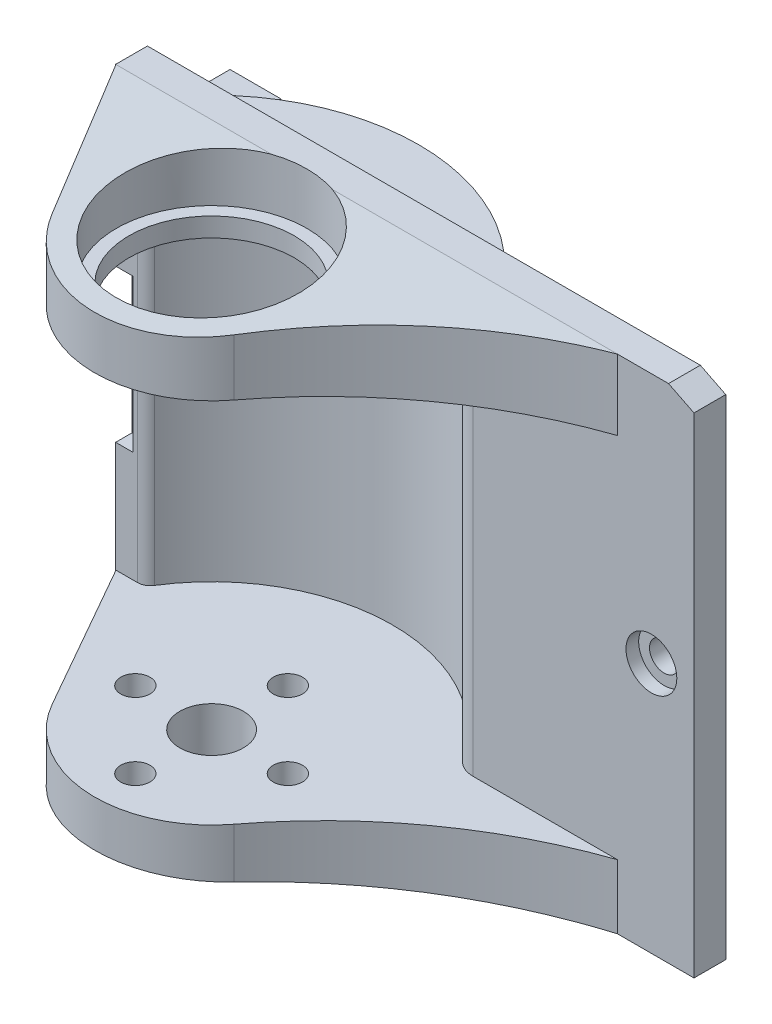
SolidWorks part; units mm, degrees
ref_plane "前视基准面" through (0, 0, 0) normal (0, 0, 1) x (1, 0, 0)
ref_plane "上视基准面" through (0, 0, 0) normal (0, 1, 0) x (1, 0, 0)
ref_plane "右视基准面" through (0, 0, 0) normal (1, 0, 0) x (0, 0, -1)
sketch "草图1" plane through (0, 0, 0) normal (0, 1, 0) x (1, 0, 0)
  circle A1 centre (0, 0) radius 16.3
  dimension "D1" = 32.6
extrude "凸台-拉伸1" add sketch "草图1" along normal mid plane 39.5
sketch "草图2" plane through (0, -19.75, 0) normal (0, -1, 0) x (1, 0, 0)
  line L1 (-14.65, -7.1) -> (31.85, -7.1)
  line L2 (-14.65, -7.1) -> (-14.65, -9.6)
  line L3 (-14.65, -9.6) -> (31.85, -9.6)
  line L4 (31.85, -7.1) -> (31.85, -9.6)
  dimension "D1" = 2.5
  dimension "D2" = 9.6
  dimension "D3" = 46.5
  dimension "D4" = 14.65
extrude "凸台-拉伸2" add sketch "草图2" against normal through all
sketch "草图3" plane through (0, -19.75, 0) normal (0, -1, 0) x (1, 0, 0)
  line L1 (31.85, -7.1) -> (-22.9944, -7.1)
  line L2 (31.85, -7.1) -> (31.85, 18.4067)
  line L3 (31.85, 18.4067) -> (-22.9944, 18.4067)
  line L4 (-22.9944, -7.1) -> (-22.9944, 18.4067)
extrude "切除-拉伸1" cut sketch "草图3" against normal blind 50
sketch "草图4" plane through (0, -19.75, 0) normal (0, -1, 0) x (1, 0, 0)
  line L0 (-14.65, -7.1462) -> (-7.9965, 4.5492)
  line L2 (-14.65, -7.1462) -> (24.85, -7.1078)
  line L3 (24.85, -7.1078) -> (24.85, 6.9283) construction
  arc A0 (7.3262, 5.5648) -> (-7.9965, 4.5492) centre (0, 0) ccw
  arc A2 (7.3262, 5.5648) -> (24.85, -7.1078) centre (36.9332, 28.0534) ccw
  dimension "D1" = 18.4
extrude "凸台-拉伸3" add sketch "草图4" against normal blind 5.05
mirror "镜向1" about plane through (0, 0, 0) normal (0, 1, 0) of "凸台-拉伸3"
sketch "草图5" plane through (0, -14.7, 0) normal (0, 1, 0) x (1, 0, 0)
  circle A0 centre (0, 0) radius 14.25
  dimension "D1" = 28.5
extrude "切除-拉伸2" cut sketch "草图5" along normal up to surface (29.4 mm away) up to face at (2.08, 14.7, -0.3156)
sketch "草图6" plane through (0, -14.7, 0) normal (0, 1, 0) x (1, 0, 0)
  circle A0 centre (0, 0) radius 2.5
  dimension "D1" = 5
extrude "切除-拉伸3" cut sketch "草图6" against normal through all
sketch "草图9" plane through (0, 19.75, 0) normal (0, 1, 0) x (1, 0, 0)
  circle A0 centre (0, 0) radius 7.5
  dimension "D1" = 15
extrude "切除-拉伸6" cut sketch "草图9" against normal up to next
sketch "草图12" plane through (0, 0, -7.1) normal (0, 0, 1) x (1, 0, 0)
  line L0 (0, 0) -> (30.0134, 0) construction
  line L1 (31.85, 19.75) -> (31.85, -19.75) construction
  circle A0 centre (27.5, 0) radius 1.15
  dimension "D1" = 2.3
  dimension "D2" = 4.35
extrude "切除-拉伸9" cut sketch "草图12" against normal through all
sketch "草图13" plane through (0, 0, -7.1) normal (0, 0, 1) x (1, 0, 0)
  circle A0 centre (27.5, 0) radius 2
  dimension "D1" = 4
extrude "切除-拉伸10" cut sketch "草图13" against normal blind 1
sketch "草图14" plane through (0, 0, -7.1) normal (0, 0, 1) x (1, 0, 0)
  line L0 (31.85, 19.75) -> (31.85, -19.75) construction
  line L1 (30.45, -6) -> (33.25, -6)
  line L2 (30.45, -6) -> (30.45, 6)
  line L3 (30.45, 6) -> (33.25, 6)
  line L4 (33.25, -6) -> (33.25, 6)
  line L5 (30.45, -6) -> (33.25, 6) construction
  line L6 (30.45, 6) -> (33.25, -6) construction
  point P0 (31.85, 0)
  dimension "12" = 12
  dimension "D2" = 2.8
extrude "切除-拉伸11" [suppressed] cut sketch "草图14" against normal blind 1.3
sketch "草图15" plane through (0, 0, -7.1) normal (0, 0, 1) x (1, 0, 0)
  line L0 (0, 0) -> (-23.1213, 0) construction
  line L1 (-14.6724, -19.75) -> (-14.6724, 19.75) construction
  line L2 (-16.0724, -6) -> (-13.2724, -6)
  line L3 (-16.0724, -6) -> (-16.0724, 6)
  line L4 (-16.0724, 6) -> (-13.2724, 6)
  line L5 (-13.2724, -6) -> (-13.2724, 6)
  line L6 (-16.0724, -6) -> (-13.2724, 6) construction
  line L7 (-16.0724, 6) -> (-13.2724, -6) construction
  point P3 (-14.6724, 0)
  dimension "D1" = 12
  dimension "D2" = 2.8
extrude "切除-拉伸12" cut sketch "草图15" against normal blind 1.3
ref_plane "基准面1" through (0, 0, -15.1) normal (0, 0, -1) x (-1, 0, 0)
sketch "草图16" plane through (0, 0, -15.1) normal (0, 0, -1) x (-1, 0, 0)
  line L0 (14.65, 19.75) -> (14.65, -19.75) construction
  line L1 (9.65, 10.9) -> (13.65, 10.9)
  line L2 (9.65, 10.9) -> (9.65, 15.9)
  line L3 (9.65, 15.9) -> (13.65, 15.9)
  line L4 (13.65, 10.9) -> (13.65, 15.9)
  line L5 (9.65, 10.9) -> (13.65, 15.9) construction
  line L6 (9.65, 15.9) -> (13.65, 10.9) construction
  line L7 (0, 0) -> (27.535, 0) construction
  point P0 (11.65, 13.4)
  dimension "D1" = 1
  dimension "D2" = 10.9
  dimension "D3" = 5
  dimension "D4" = 4
extrude "凸台-拉伸5" add sketch "草图16" against normal up to surface (1.9635 mm away)
mirror "镜向4" about plane through (0, 0, 0) normal (0, 1, 0) of "凸台-拉伸5"
sketch "草图17" plane through (0, 0, -15.1) normal (0, 0, -1) x (-1, 0, 0)
  line L0 (11.65, 15.9) -> (11.65, 12.48) construction
  line L1 (13.65, 15.9) -> (9.65, 15.9) construction
  line L2 (13.65, 13.4) -> (11.1035, 13.4) construction
  line L3 (13.65, 10.9) -> (13.65, 15.9) construction
  line L5 (11.15, 12.4) -> (12.15, 12.4)
  line L6 (11.15, 12.4) -> (11.15, 14.4)
  line L7 (11.15, 14.4) -> (12.15, 14.4)
  line L8 (12.15, 12.4) -> (12.15, 14.4)
  line L9 (11.15, 12.4) -> (12.15, 14.4) construction
  line L10 (11.15, 14.4) -> (12.15, 12.4) construction
  point P8 (11.65, 13.4)
  dimension "D1" = 2
  dimension "D2" = 1
extrude "切除-拉伸13" cut sketch "草图17" against normal blind 2.5
mirror "镜向5" about plane through (0, 0, 0) normal (0, 1, 0) of "切除-拉伸13"
sketch "草图19" plane through (0, 19.75, 0) normal (0, 1, 0) x (1, 0, 0)
  circle A1 centre (0, 0) radius 6.5
  circle A2 centre (0, 0) radius 8.519
  dimension "D1" = 13
extrude "凸台-拉伸6" add sketch "草图19" against normal blind 2.25
sketch "草图20" plane through (0, -19.75, 0) normal (0, -1, 0) x (1, 0, 0)
  circle A0 centre (0, 6) radius 1.15
  dimension "D1" = 2.3
  dimension "D2" = 6
extrude "切除-拉伸18" cut sketch "草图20" against normal up to next
pattern_circular "阵列(圆周)1" count 4 over 360 about axis through (0, 0, 0) along (0, 1, 0) of "切除-拉伸18"
sketch "草图7" plane through (-14.65, 0, 0) normal (-1, 0, 0) x (0, 0, 1)
  line L0 (-7.1, 19.75) -> (9.2, 18.3239)
  line L1 (9.2, 14.7) -> (9.2, 19.75) construction
  line L2 (9.2, 18.3239) -> (9.2, 19.75)
  line L3 (9.2, 19.75) -> (-7.1, 19.75)
  dimension "D1" = 5
extrude "切除-拉伸8" cut sketch "草图7" against normal through all
mirror "镜向3" about plane through (0, 0, 0) normal (0, 1, 0) of "切除-拉伸8"
sketch "草图18" plane through (0, 0, -9.6) normal (0, 0, -1) x (-1, 0, 0)
  line L0 (-13.1731, 19.75) -> (-13.1731, -19.75) construction
  line L1 (13.1731, 19.75) -> (-13.1731, 19.75)
  line L2 (13.1731, 19.75) -> (13.1731, 17)
  line L3 (13.1731, 17) -> (-13.1731, 17)
  line L4 (-13.1731, 19.75) -> (-13.1731, 17)
  dimension "D1" = 2.75
extrude "切除-拉伸16" cut sketch "草图18" along normal blind 12.5
mirror "镜向6" about plane through (0, 0, 0) normal (0, 1, 0) of "切除-拉伸16"
fillet "圆角1" radius 2 1 edges at (12.3553, 0, -7.1)
fillet "圆角2" radius 1 1 edges at (-12.3553, 0, -7.1)
sketch "草图21" plane through (0, -19.75, 0) normal (0, -1, 0) x (1, 0, 0)
  circle A0 centre (0, 6) radius 2.1
  circle A1 centre (-6, 0) radius 2.1
  circle A2 centre (6, 0) radius 2.1
  circle A3 centre (0, -6) radius 2.1
  dimension "D1" = 4.2
extrude "切除-拉伸19" cut sketch "草图21" against normal blind 2.5
sketch "草图22" plane through (0, 17.5, 0) normal (0, -1, 0) x (1, 0, 0)
  circle A0 centre (0, 0) radius 7.5
  dimension "D1" = 15
extrude "切除-拉伸23" cut sketch "草图22" against normal blind 10
sketch "草图23" plane through (0, 14.7, 0) normal (0, -1, 0) x (1, 0, 0)
  circle A0 centre (0, 0) radius 6.5
  circle A2 centre (0, 0) radius 7.5
  dimension "D1" = 13
  dimension "D2" = 15
extrude "凸台-拉伸7" add sketch "草图23" against normal blind 1
other "移动面3" face at (1.0542, 14.7, -4.6461) parameters "D1"=0.5
sketch "草图27" plane through (0, 0, -7.1) normal (0, 0, 1) x (1, 0, 0)
  line L0 (31.85, -19.75) -> (24.8274, -19.75) construction
  line L1 (31.85, 19.75) -> (30.85, 19.75)
  line L2 (31.85, 19.75) -> (31.85, -19.75)
  line L3 (31.85, -19.75) -> (30.85, -19.75)
  line L4 (30.85, 19.75) -> (30.85, -19.75)
  dimension "D1" = 1
extrude "切除-拉伸24" cut sketch "草图27" against normal through all
chamfer "倒角1" distance 2 distance2 1 1 edges at (30.85, 19.75, -8.35)
sketch "草图29" plane through (0, 0, -7.1) normal (0, 0, 1) x (1, 0, 0)
  line L0 (0, 0) -> (1.2489, 0) construction
